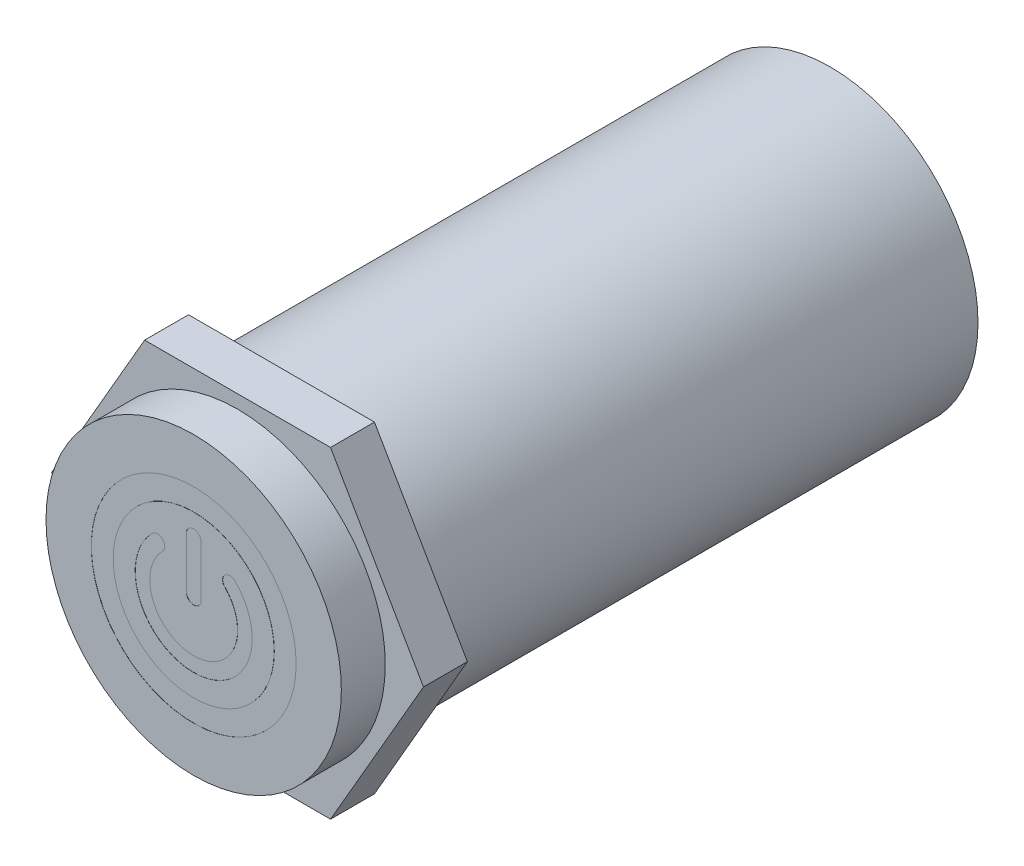
SolidWorks part; units mm, degrees
ref_plane "前视基准面" through (0, 0, 0) normal (0, 0, 1) x (1, 0, 0)
ref_plane "上视基准面" through (0, 0, 0) normal (0, 1, 0) x (1, 0, 0)
ref_plane "右视基准面" through (0, 0, 0) normal (1, 0, 0) x (0, 0, -1)
sketch "草图1" plane through (0, 0, 0) normal (0, 0, 1) x (1, 0, 0)
  line L1 (12.7017, 0) -> (6.3509, 11)
  line L2 (6.3509, 11) -> (-6.3509, 11)
  line L3 (-6.3509, 11) -> (-12.7017, 0)
  line L4 (-12.7017, 0) -> (-6.3509, -11)
  line L5 (-6.3509, -11) -> (6.3509, -11)
  line L6 (6.3509, -11) -> (12.7017, 0)
  circle A0 centre (0, 0) radius 11 construction
extrude "凸台-拉伸1" add sketch "草图1" along normal blind 3
sketch "草图3" plane through (0, 0, 3) normal (0, 0, 1) x (1, 0, 0)
  circle A0 centre (0, 0) radius 10.09
extrude "凸台-拉伸2" add sketch "草图3" along normal blind 3 and the other way blind 40.5
sketch "草图5" plane through (0, 0, 6) normal (0, 0, 1) x (1, 0, 0)
  line L3 (-0.5, 0.5) -> (-0.5, 4)
  line L5 (0.5, 4) -> (0.5, 0.5)
  circle A0 centre (0, 0) radius 7
  arc A1 (-2.8284, 2.8284) -> (2.8284, 2.8284) centre (0, 0) ccw
  arc A2 (-2.1213, 2.1213) -> (2.1213, 2.1213) centre (0, 0) ccw
  arc A3 (2.8284, 2.8284) -> (2.1213, 2.1213) centre (2.4749, 2.4749) ccw
  arc A4 (-2.8284, 2.8284) -> (-2.1213, 2.1213) centre (-2.4749, 2.4749) cw
  arc A5 (0.5, 4) -> (-0.5, 4) centre (0, 4) ccw
  arc A6 (-0.5, 0.5) -> (0.5, 0.5) centre (0, 0.5) ccw
  circle A7 centre (0, 0) radius 5.5
extrude "切除-拉伸1" cut sketch "草图5" against normal blind 0.01 contours A0 A7 | A4 A1 A3 A2 | L3 A5 L5 A6
